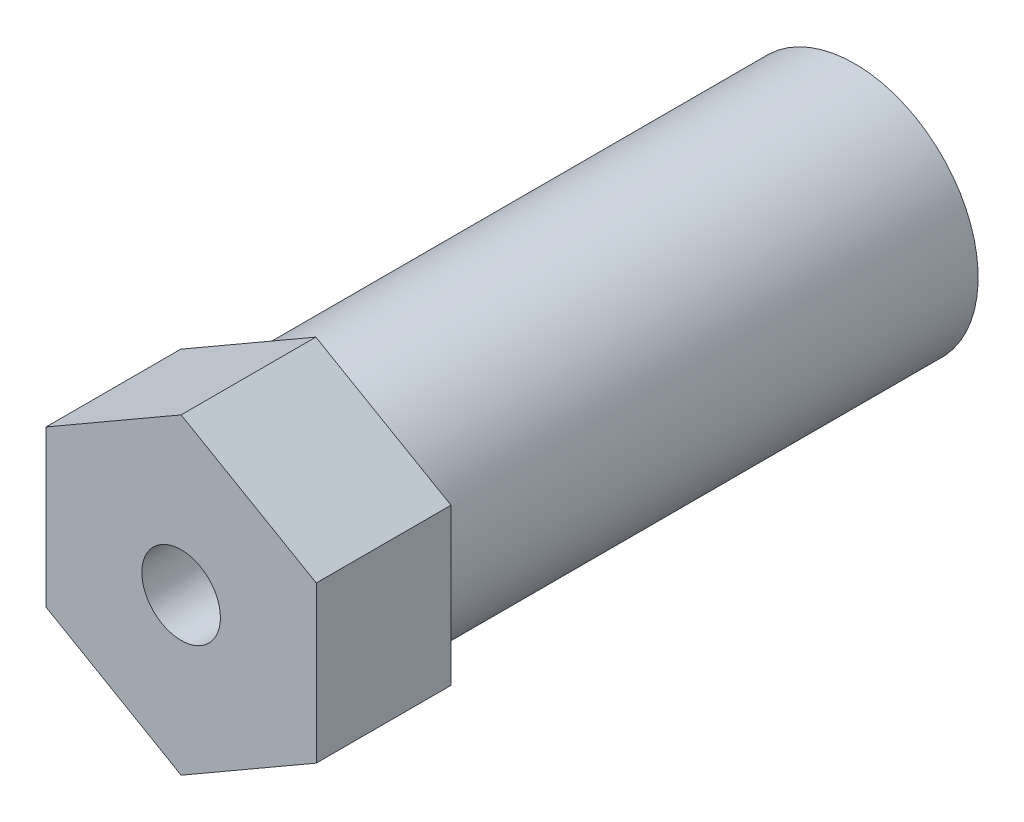
SolidWorks part; units mm, degrees
ref_plane "Front Plane" through (0, 0, 0) normal (0, 0, 1) x (1, 0, 0)
ref_plane "Top Plane" through (0, 0, 0) normal (0, 1, 0) x (1, 0, 0)
ref_plane "Right Plane" through (0, 0, 0) normal (1, 0, 0) x (0, 0, -1)
sketch "Sketch2" plane through (0, 0, 0) normal (0, 0, 1) x (1, 0, 0)
  line L2 (0, 6.95) -> (-6.0189, 3.475)
  line L3 (-6.0189, 3.475) -> (-6.0189, -3.475)
  line L4 (-6.0189, -3.475) -> (0, -6.95)
  line L5 (0, -6.95) -> (6.0189, -3.475)
  line L6 (6.0189, -3.475) -> (6.0189, 3.475)
  line L7 (6.0189, 3.475) -> (0, 6.95)
  circle A0 centre (0, 0) radius 6.0189 construction
extrude "Boss-Extrude1" add sketch "Sketch2" along normal blind 6
sketch "Sketch3" plane through (0, 0, 6) normal (0, 0, 1) x (1, 0, 0)
  circle A0 centre (0, 0) radius 1.75
extrude "Cut-Extrude1" cut sketch "Sketch3" against normal blind 6
sketch "Sketch4" plane through (0, 0, 0) normal (0, 0, -1) x (-1, 0, 0)
  circle A0 centre (0, 0) radius 5.5
  circle A1 centre (0, 0) radius 3
extrude "Boss-Extrude2" add sketch "Sketch4" along normal blind 24
